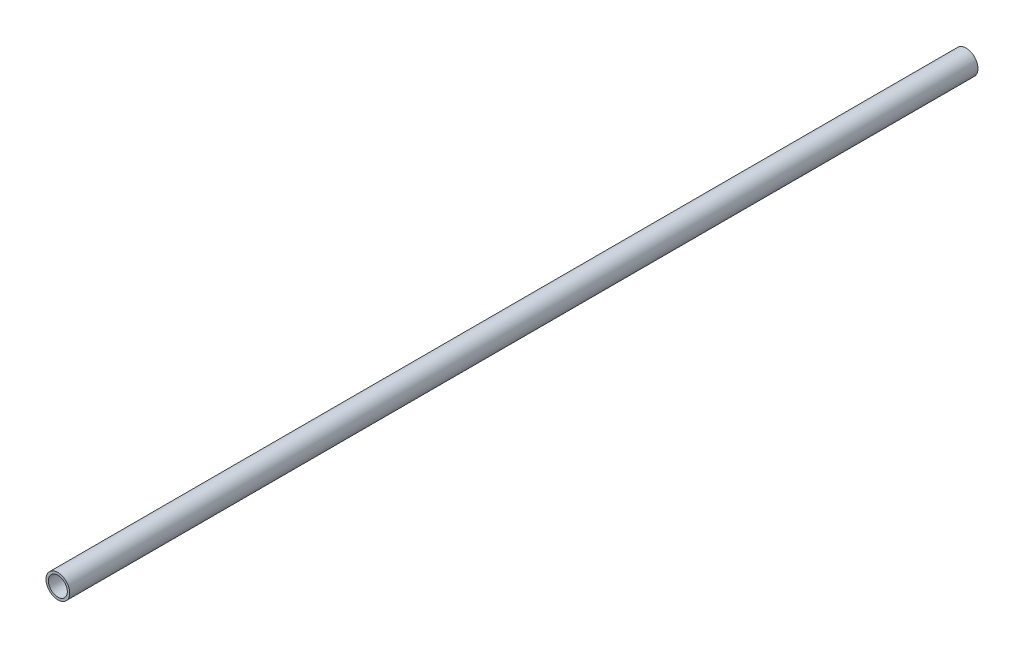
SolidWorks part; units mm, degrees
material "Cast Carbon Steel"
ref_plane "Front Plane" through (0, 0, 0) normal (0, 0, 1) x (1, 0, 0)
ref_plane "Top Plane" through (0, 0, 0) normal (0, 1, 0) x (1, 0, 0)
ref_plane "Right Plane" through (0, 0, 0) normal (1, 0, 0) x (0, 0, -1)
sketch "Sketch1" plane through (0, 0, 0) normal (0, 0, 1) x (1, 0, 0)
  circle A0 centre (0, 0) radius 13.3223
  circle A1 centre (0, 0) radius 16.7005
extrude "Boss-Extrude1" add sketch "Sketch1" against normal blind 1278.128
